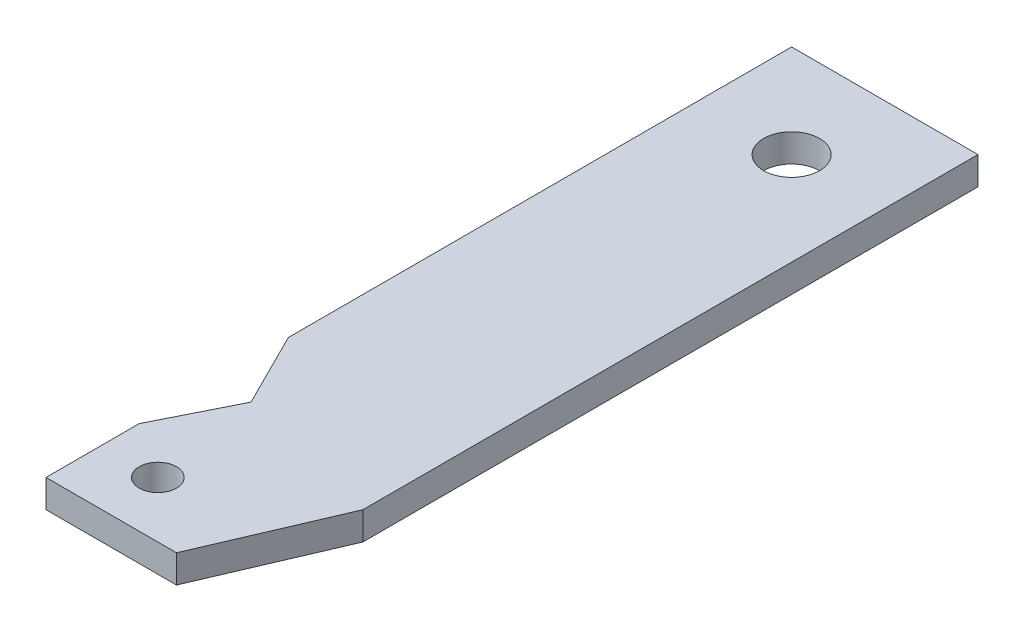
SolidWorks part; units mm, degrees
ref_plane "Plan de face" through (0, 0, 0) normal (0, 0, 1) x (1, 0, 0)
ref_plane "Plan de dessus" through (0, 0, 0) normal (0, 1, 0) x (1, 0, 0)
ref_plane "Plan de droite" through (0, 0, 0) normal (1, 0, 0) x (0, 0, -1)
sketch "Esquisse1" plane through (0, 0, 0) normal (0, 0, 1) x (1, 0, 0)
  line L1 (-12.7726, 11.5904) -> (-2.7726, 11.5904)
  line L2 (-12.7726, 11.5904) -> (-12.7726, 10.0904)
  line L3 (-12.7726, 10.0904) -> (-2.7726, 10.0904)
  line L4 (-2.7726, 11.5904) -> (-2.7726, 10.0904)
  dimension "D1" = 10
  dimension "D2" = 1.5
extrude "Extrusion1" add sketch "Esquisse1" along normal blind 40
sketch "Esquisse2" plane through (0, 11.5904, 0) normal (0, 1, 0) x (-1, 0, 0)
  line L0 (2.7726, 40) -> (2.7726, 0) construction
  line L1 (2.7726, 40) -> (12.7726, 40) construction
  line L2 (2.7726, 0) -> (12.7726, 0) construction
  line L3 (12.7726, 35) -> (10.7726, 31)
  line L4 (12.7726, 40) -> (12.7726, 0) construction
  line L5 (10.7726, 31) -> (12.7726, 27)
  line L6 (12.7726, 35) -> (12.7726, 27)
  line L7 (5.7726, 40) -> (2.7726, 40)
  line L8 (2.7726, 40) -> (2.7726, 33)
  line L9 (2.7726, 33) -> (5.7726, 40)
  circle A0 centre (9.7726, 37) radius 1
  circle A1 centre (7.7726, 5) radius 1.5
  dimension "D1" = 7
  dimension "D3" = 5
  dimension "D2" = 3
  dimension "D4" = 5
  dimension "D5" = 8
  dimension "D6" = 5
  dimension "D7" = 2
  dimension "D8" = 4
  dimension "D9" = 3
  dimension "D10" = 7
extrude "Extrusion2" cut sketch "Esquisse2" against normal blind 50
